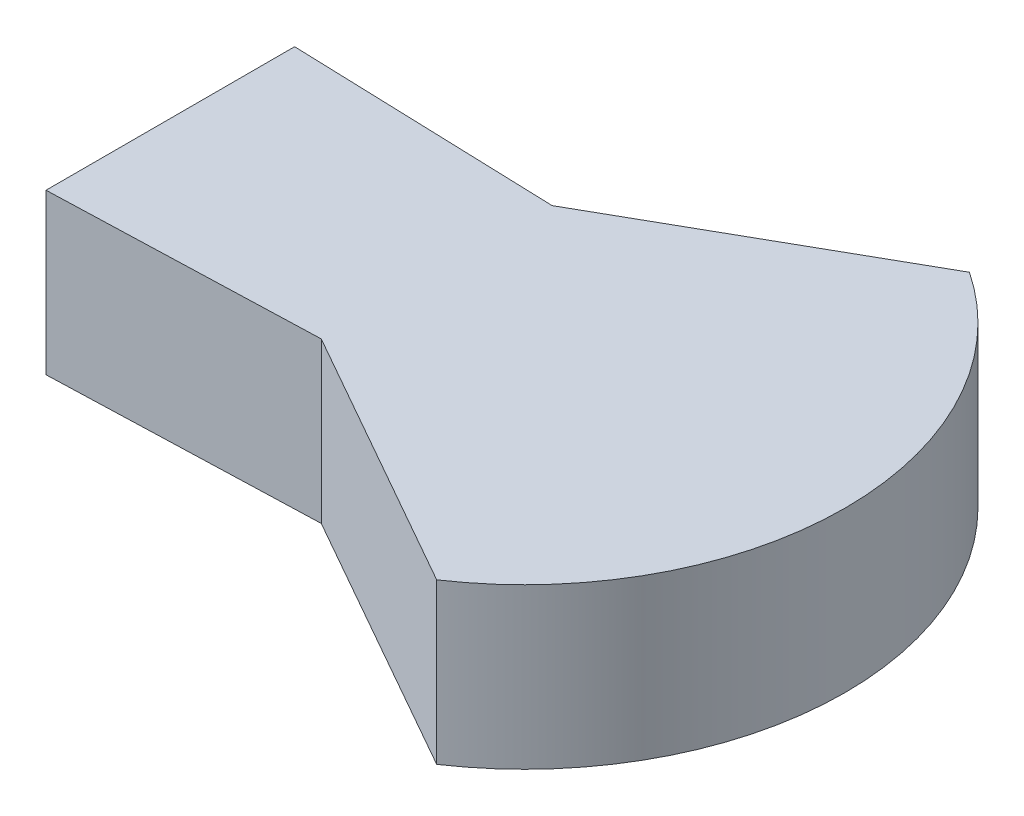
SolidWorks part; units mm, degrees
ref_plane "Front Plane" through (0, 0, 0) normal (0, 0, 1) x (1, 0, 0)
ref_plane "Top Plane" through (0, 0, 0) normal (0, 1, 0) x (1, 0, 0)
ref_plane "Right Plane" through (0, 0, 0) normal (1, 0, 0) x (0, 0, -1)
sketch "Sketch1" plane through (0, 0, 0) normal (0, 1, 0) x (1, 0, 0)
  line L0 (-7.5, 3.5) -> (-7.5, -3.5)
  line L1 (-7.5, -3.5) -> (7.5, -3)
  line L2 (7.5, -3) -> (7.5, 3)
  line L3 (7.5, 3) -> (-7.5, 3.5)
  line L4 (-7.5, 0) -> (7.5, 0) construction
  point P6 (0, 0)
  dimension "D1" = 7
  dimension "D2" = 6
  dimension "D3" = 15
extrude "Boss-Extrude1" add sketch "Sketch1" along normal blind 3
sketch "Sketch2" plane through (0, 0, 0) normal (0, -1, 0) x (1, 0, 0)
  line L0 (-7.5, 2.375) -> (-7.5, -2.375)
  line L1 (-7.5, -3.5) -> (-7.5, 3.5) construction
  line L2 (-7.5, -2.375) -> (-0.0323, -2.025)
  line L3 (-7.5, 2.375) -> (-0.0323, 2.025)
  line L4 (-7.5, 0) -> (1.9, 0) construction
  arc A0 (-0.0323, -2.025) -> (-0.0323, 2.025) centre (-0.1272, 0) ccw
  point P7 (-7.5, 0)
  point P10 (0, 0)
  dimension "D1" = 4.75
  dimension "D2" = 4.05
  dimension "D3" = 9.4
extrude "Cut-Extrude1" cut sketch "Sketch2" against normal blind 1.5
sketch "Sketch4" plane through (0, 0, 0) normal (0, -1, 0) x (1, 0, 0)
  line L4 (-7.5, -3.5) -> (7.5, -3)
  line L5 (-7.5, 3.5) -> (-7.5, -3.5)
  line L6 (7.5, 3) -> (-7.5, 3.5)
  line L7 (7.5, -3) -> (7.5, 3)
  line L8 (-7.5, -3.5) -> (7.5, -3)
  line L9 (-7.5, 3.5) -> (-7.5, -3.5)
  line L10 (7.5, 3) -> (-7.5, 3.5)
  line L11 (7.5, -3) -> (7.5, 3)
  dimension "D1" = 0
extrude "Boss-Extrude2" add sketch "Sketch4" along normal blind 1.5
sketch "Sketch6" plane through (0, 3, 0) normal (0, 1, 0) x (1, 0, 0)
  line L0 (7.5, 7.5) -> (7.5, -7.5)
  line L2 (7.5, -3) -> (7.5, 3) construction
  arc A1 (7.5, -7.5) -> (7.5, 7.5) centre (2.4688, 0) ccw
  point P4 (7.5, 0)
  point P5 (7.5, 0)
  point P7 (11.5, 0)
  dimension "D1" = 15
  dimension "D2" = 4
extrude "Boss-Extrude3" add sketch "Sketch6" against normal up to surface (4.5 mm away) up to face at (0, -1.5, 0)
sketch "Sketch7" plane through (0, -1.5, 0) normal (0, -1, 0) x (1, 0, 0)
  line L0 (7.5, 7.5) -> (0, 3.25)
  line L1 (7.5, 3) -> (-7.5, 3.5) construction
  line L2 (0, 3.25) -> (7.5, 3)
  line L3 (7.5, 3) -> (7.5, 7.5)
extrude "Boss-Extrude4" add sketch "Sketch7" against normal up to surface (4.5 mm away) up to face at (3.1667, 3, 0)
mirror "Mirror1" about plane through (0, 0, 0) normal (0, 0, 1) of "Boss-Extrude4"
